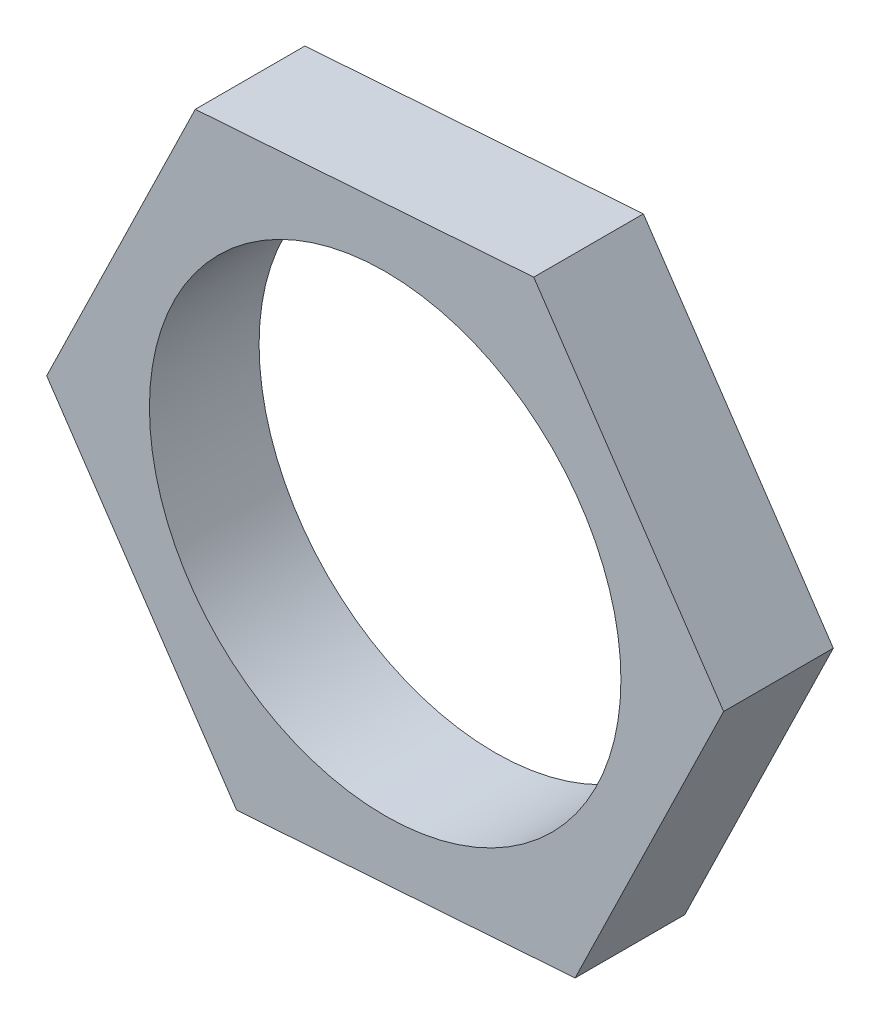
SolidWorks part; units mm, degrees
ref_plane "Front Plane" through (0, 0, 0) normal (0, 0, 1) x (1, 0, 0)
ref_plane "Top Plane" through (0, 0, 0) normal (0, 1, 0) x (1, 0, 0)
ref_plane "Right Plane" through (0, 0, 0) normal (1, 0, 0) x (0, 0, -1)
sketch "Sketch1" plane through (0, 0, 0) normal (0, 0, 1) x (1, 0, 0)
  line L1 (6.7745, 13.9111) -> (-8.6601, 12.8225)
  line L2 (-8.6601, 12.8225) -> (-15.4346, -1.0887)
  line L3 (-15.4346, -1.0887) -> (-6.7745, -13.9111)
  line L4 (-6.7745, -13.9111) -> (8.6601, -12.8225)
  line L5 (8.6601, -12.8225) -> (15.4346, 1.0887)
  line L6 (15.4346, 1.0887) -> (6.7745, 13.9111)
  circle A0 centre (0, 0) radius 13.4 construction
  circle A1 centre (0, 0) radius 10.75
  dimension "D2" = 26.8
  dimension "D3" = 21.5
  dimension "D1" = 8.6601
extrude "Boss-Extrude1" add sketch "Sketch1" along normal blind 5
